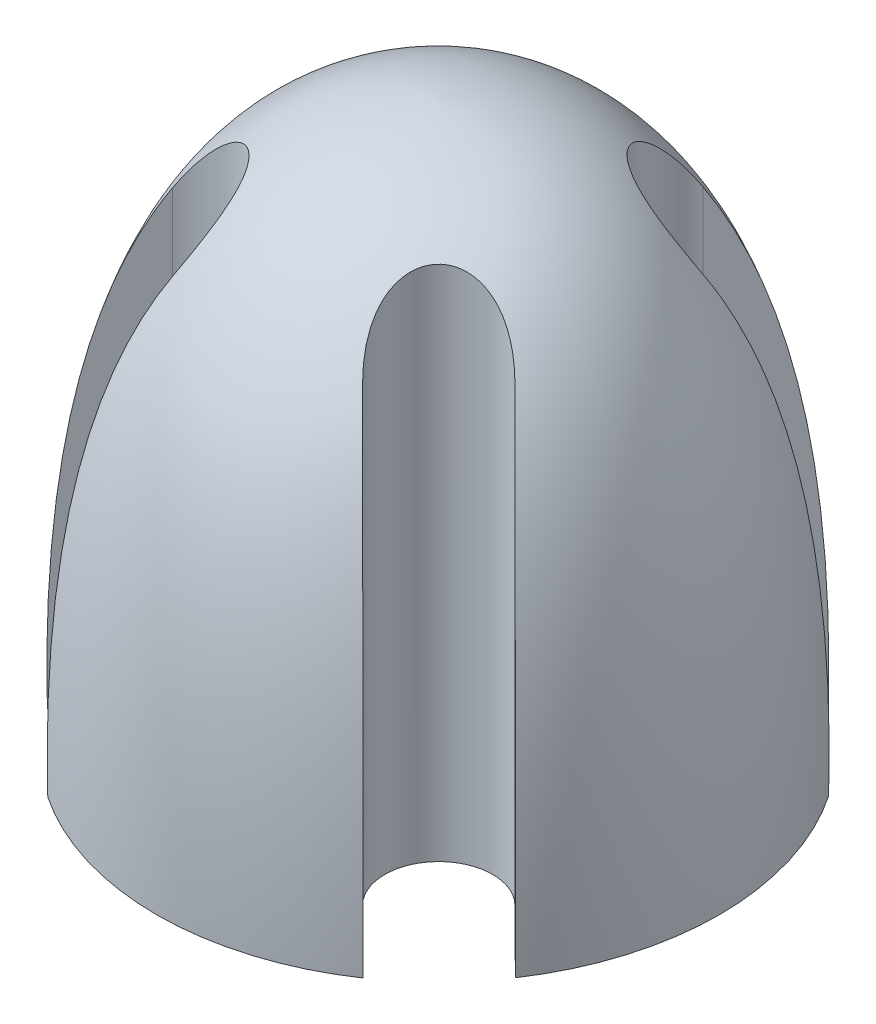
SolidWorks part; units mm, degrees
ref_plane "Front Plane" through (0, 0, 0) normal (0, 0, 1) x (1, 0, 0)
ref_plane "Top Plane" through (0, 0, 0) normal (0, 1, 0) x (1, 0, 0)
ref_plane "Right Plane" through (0, 0, 0) normal (1, 0, 0) x (0, 0, -1)
sketch "Sketch1" plane through (0, 0, 0) normal (0, 0, 1) x (1, 0, 0)
  line L0 (0, 0) -> (0, 38.1)
  line L1 (0, 0) -> (19.05, 0)
  spline S0 degree 2 poles (0, 38.1) (19.7531, 37.1284) (19.05, 0) knots 0 0 0 1 1 1
  dimension "D1" = 19.05
  dimension "D2" = 38.1
revolve "Revolve1" add sketch "Sketch1" angle 360 about L0
sketch "Sketch3" plane through (0, 0, 0) normal (0, -1, 0) x (1, 0, 0)
  circle A0 centre (12.7, 0) radius 2
  circle A1 centre (-12.7, 0) radius 2
  circle A2 centre (0, 12.7) radius 2
  circle A3 centre (0, -12.7) radius 2
  dimension "D1" = 4
  dimension "D2" = 4
  dimension "D3" = 4
  dimension "D4" = 4
  dimension "D9" = 12.7
  dimension "D11" = 12.7
  dimension "D5" = 0
  dimension "D6" = 0
  dimension "D7" = 0
  dimension "D8" = 0
  dimension "D10" = 12.7
  dimension "D12" = 12.7
extrude "Cut-Extrude1" cut sketch "Sketch3" against normal blind 7
sketch "Sketch4" plane through (0, 0, 0) normal (0, -1, 0) x (1, 0, 0)
  line L4 (18.011, 17.9098) -> (9.0055, 8.9549) construction
  line L7 (20.5851, 15.3213) -> (11.5795, 6.3664)
  line L10 (15.437, 20.4984) -> (6.4315, 11.5435)
  line L14 (17.9098, -18.011) -> (8.9549, -9.0055) construction
  line L15 (15.3213, -20.5851) -> (6.3664, -11.5795)
  line L16 (20.4984, -15.437) -> (11.5435, -6.4315)
  line L17 (-18.011, -17.9098) -> (-9.0055, -8.9549) construction
  line L18 (-20.5851, -15.3213) -> (-11.5795, -6.3664)
  line L19 (-15.437, -20.4984) -> (-6.4315, -11.5435)
  line L20 (-17.9098, 18.011) -> (-8.9549, 9.0055) construction
  line L21 (-15.3213, 20.5851) -> (-6.3664, 11.5795)
  line L22 (-20.4984, 15.437) -> (-11.5435, 6.4315)
  arc A1 (20.5851, 15.3213) -> (15.437, 20.4984) centre (18.011, 17.9098) ccw
  arc A18 (6.4315, 11.5435) -> (11.5795, 6.3664) centre (9.0055, 8.9549) ccw
  arc A26 (15.3213, -20.5851) -> (20.4984, -15.437) centre (17.9098, -18.011) ccw
  arc A27 (11.5435, -6.4315) -> (6.3664, -11.5795) centre (8.9549, -9.0055) ccw
  arc A28 (-20.5851, -15.3213) -> (-15.437, -20.4984) centre (-18.011, -17.9098) ccw
  arc A29 (-6.4315, -11.5435) -> (-11.5795, -6.3664) centre (-9.0055, -8.9549) ccw
  arc A30 (-15.3213, 20.5851) -> (-20.4984, 15.437) centre (-17.9098, 18.011) ccw
  arc A31 (-11.5435, 6.4315) -> (-6.3664, 11.5795) centre (-8.9549, 9.0055) ccw
  point P5 (13.5083, 13.4324)
  point P19 (0, 0)
  point P29 (0, 0)
  point P33 (13.4324, -13.5083)
  point P40 (-13.5083, -13.4324)
  point P47 (-13.4324, 13.5083)
  point P52 (0, 0)
  point P53 (0, 0)
  dimension "D1" = 3.6505
  dimension "D4" = 4
extrude "Cut-Extrude3" cut sketch "Sketch4" against normal up to next
